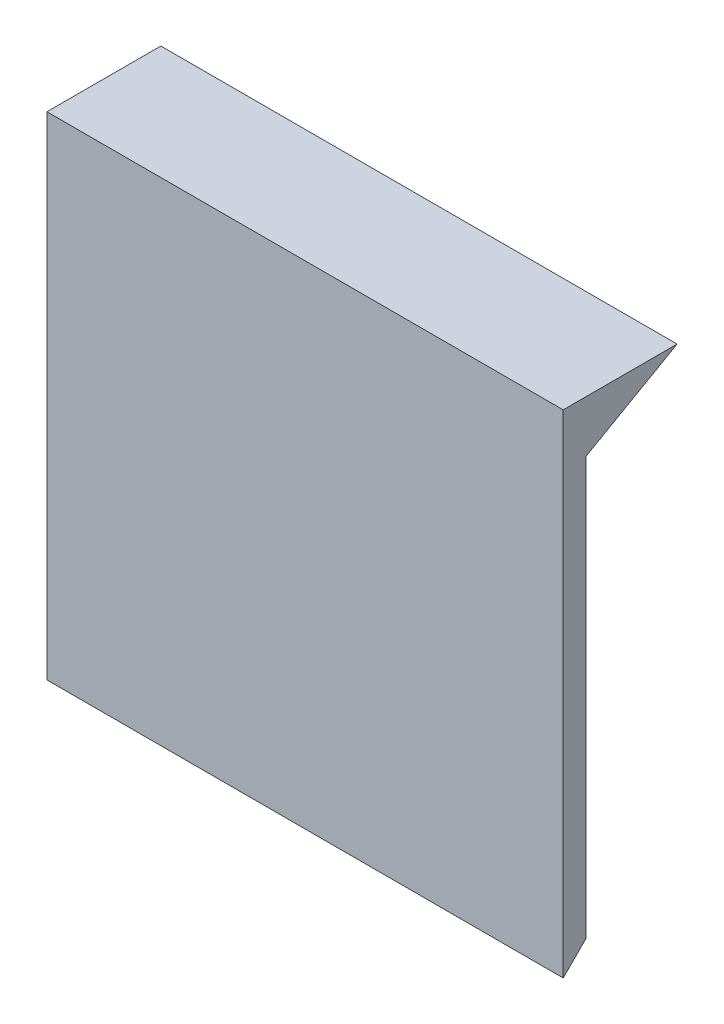
SolidWorks part; units mm, degrees
ref_plane "Alzado" through (0, 0, 0) normal (0, 0, 1) x (1, 0, 0)
ref_plane "Planta" through (0, 0, 0) normal (0, 1, 0) x (1, 0, 0)
ref_plane "Vista lateral" through (0, 0, 0) normal (1, 0, 0) x (0, 0, -1)
sketch "Croquis1" plane through (0, 0, 0) normal (0, 0, 1) x (1, 0, 0)
  line L1 (-34, 27.5) -> (34, 27.5)
  line L2 (-34, 27.5) -> (-34, -27.5)
  line L3 (-34, -27.5) -> (34, -27.5)
  line L4 (34, 27.5) -> (34, -27.5)
  line L5 (-34, 27.5) -> (34, -27.5) construction
  line L6 (-34, -27.5) -> (34, 27.5) construction
  point P0 (0, 0)
  dimension "D1" = 68
  dimension "D2" = 55
extrude "Saliente-Extruir1" add sketch "Croquis1" along normal blind 3
sketch "Croquis2" plane through (-34, 0, 0) normal (-1, 0, 0) x (0, 0, 1)
  line L0 (3, -27.5) -> (3, -30.5)
  line L1 (3, -30.5) -> (0, -27.5)
  line L2 (0, -27.5) -> (3, -27.5)
  dimension "D1" = 45
extrude "Saliente-Extruir2" add sketch "Croquis2" against normal through all
sketch "Croquis3" plane through (34, 0, 0) normal (1, 0, 0) x (0, 0, -1)
  line L0 (0, 27.5) -> (12, 34.3066)
  line L1 (12, 34.3066) -> (-3, 34.3066)
  line L2 (-3, 34.3066) -> (-3, 27.5)
  line L3 (-3, 27.5) -> (0, 27.5)
  line L4 (-3, -30.5) -> (-3, 27.5) construction
  point P3 (0, 0)
  dimension "D1" = 15
  dimension "D2" = 29.562
extrude "Saliente-Extruir3" add sketch "Croquis3" against normal through all
sketch "Croquis4" plane through (0, 20.8061, 11.8015) normal (0, -0.8698, -0.4934) x (1, 0, 0)
  line L0 (-34, -20.4657) -> (34, -20.4657) construction
  line L1 (-34, -13.5677) -> (-34, -27.3637) construction
  line L2 (34, -13.5677) -> (34, -27.3637) construction
  text T0 "<b>OSCILADOR CLAPP</b>" font "Century Gothic" height 4
extrude "Cortar-Extruir1" cut sketch "Croquis4" against normal blind 1
